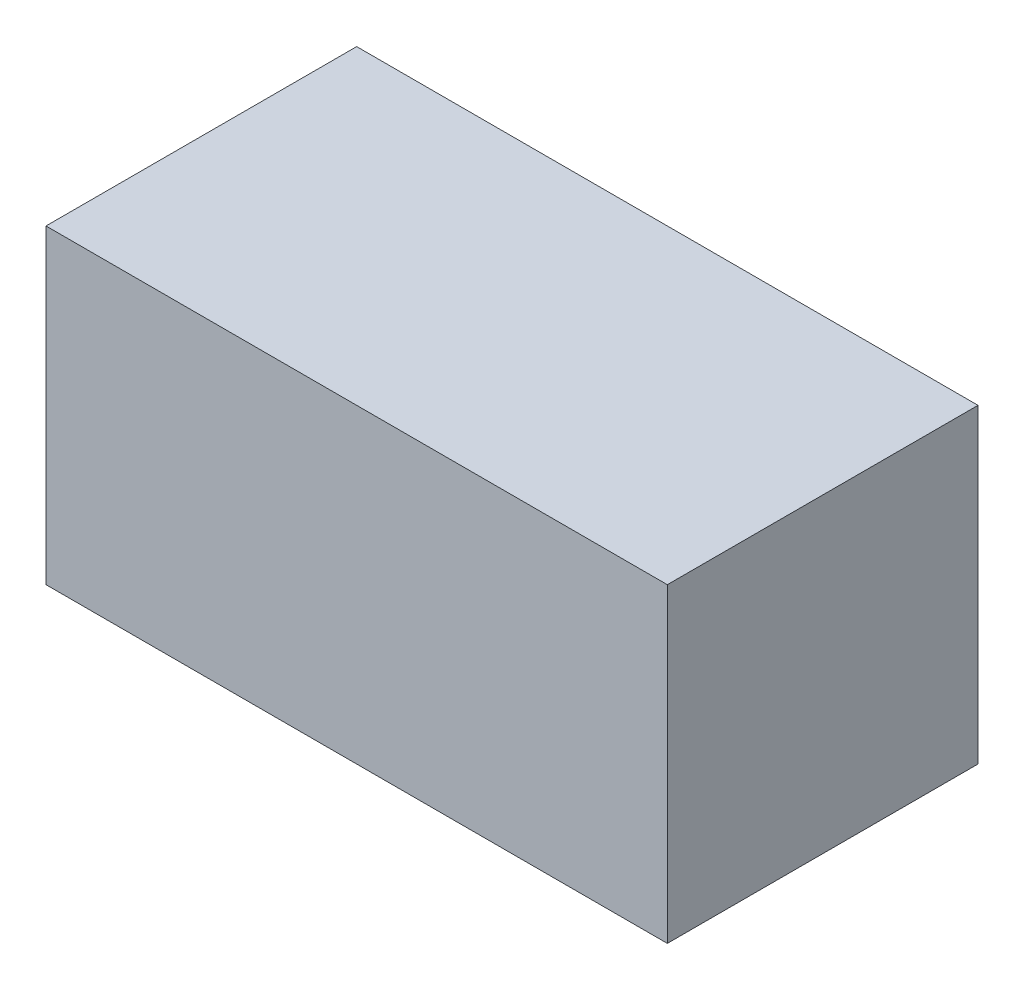
SolidWorks part; units mm, degrees
ref_plane "Front Plane" through (0, 0, 0) normal (0, 0, 1) x (1, 0, 0)
ref_plane "Top Plane" through (0, 0, 0) normal (0, 1, 0) x (1, 0, 0)
ref_plane "Right Plane" through (0, 0, 0) normal (1, 0, 0) x (0, 0, -1)
sketch "Esquisse1" plane through (0, 0, 0) normal (0, 0, 1) x (1, 0, 0)
  line L1 (-57.228, 26.2141) -> (42.772, 26.2141)
  line L2 (-57.228, 26.2141) -> (-57.228, -23.7859)
  line L3 (-57.228, -23.7859) -> (42.772, -23.7859)
  line L4 (42.772, 26.2141) -> (42.772, -23.7859)
  line L5 (-57.228, 26.2141) -> (42.772, -23.7859) construction
  line L6 (-57.228, -23.7859) -> (42.772, 26.2141) construction
  point P0 (-7.228, 1.2141)
  dimension "D1" = 100
  dimension "D2" = 50
extrude "Extrusion1" add sketch "Esquisse1" along normal blind 50
